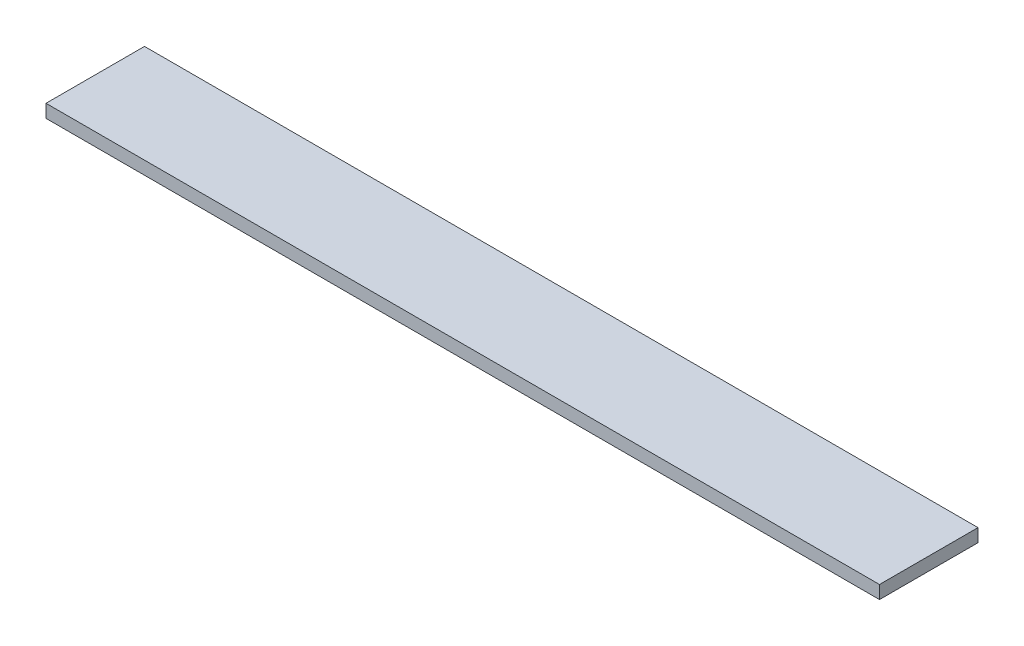
SolidWorks part; units mm, degrees
ref_plane "Front Plane" through (0, 0, 0) normal (0, 0, 1) x (1, 0, 0)
ref_plane "Top Plane" through (0, 0, 0) normal (0, 1, 0) x (1, 0, 0)
ref_plane "Right Plane" through (0, 0, 0) normal (1, 0, 0) x (0, 0, -1)
sketch "Sketch1" plane through (0, 0, 0) normal (0, 1, 0) x (1, 0, 0)
  line L1 (-541.5, 64) -> (541.5, 64)
  line L2 (-541.5, 64) -> (-541.5, -64)
  line L3 (-541.5, -64) -> (541.5, -64)
  line L4 (541.5, 64) -> (541.5, -64)
  line L5 (-541.5, 64) -> (541.5, -64) construction
  line L6 (-541.5, -64) -> (541.5, 64) construction
  point P0 (0, 0)
  dimension "D1" = 1083
  dimension "D2" = 128
extrude "Boss-Extrude1" add sketch "Sketch1" along normal blind 17
